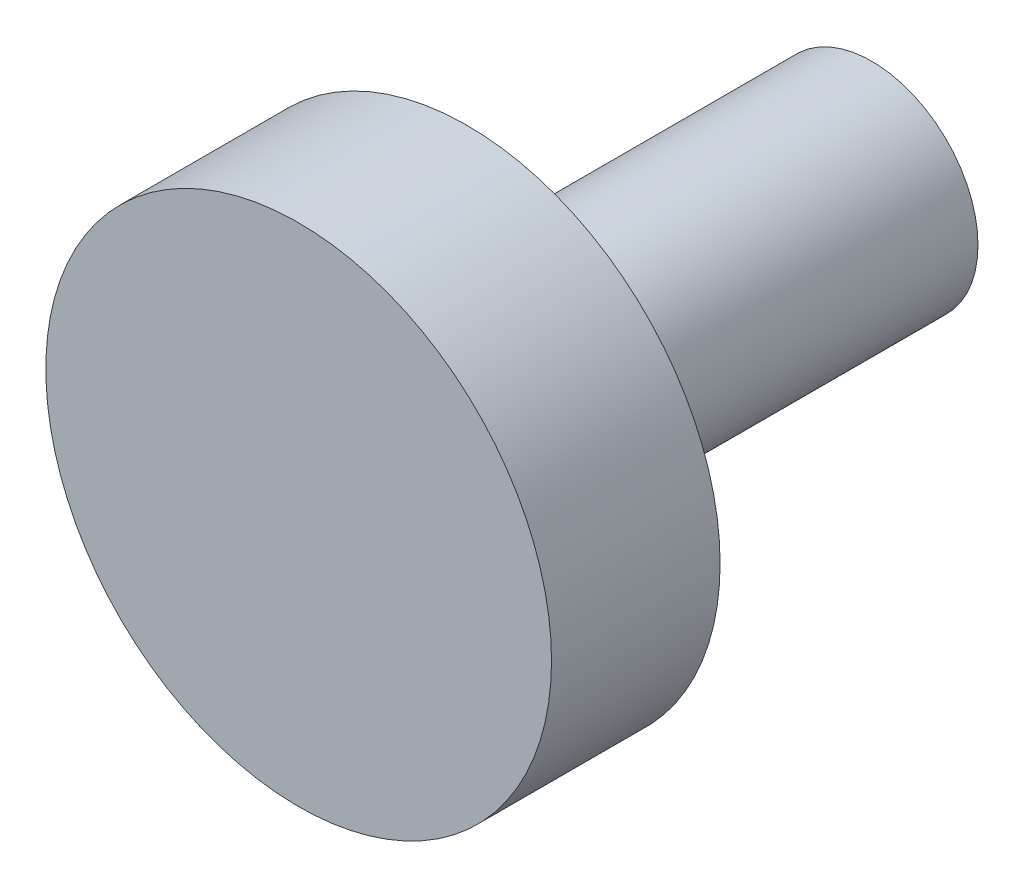
SolidWorks part; units mm, degrees
ref_plane "Front Plane" through (0, 0, 0) normal (0, 0, 1) x (1, 0, 0)
ref_plane "Top Plane" through (0, 0, 0) normal (0, 1, 0) x (1, 0, 0)
ref_plane "Right Plane" through (0, 0, 0) normal (1, 0, 0) x (0, 0, -1)
sketch "Sketch1" plane through (0, 0, 0) normal (0, 0, 1) x (1, 0, 0)
  circle A0 centre (0, 0) radius 9.525
  dimension "D1" = 19.05
extrude "Boss-Extrude1" add sketch "Sketch1" along normal blind 6.35
sketch "Sketch2" plane through (0, 0, 0) normal (0, 0, 1) x (1, 0, 0)
  circle A0 centre (0, 0) radius 4
  dimension "D1" = 8
extrude "Boss-Extrude2" add sketch "Sketch2" against normal blind 15.24
